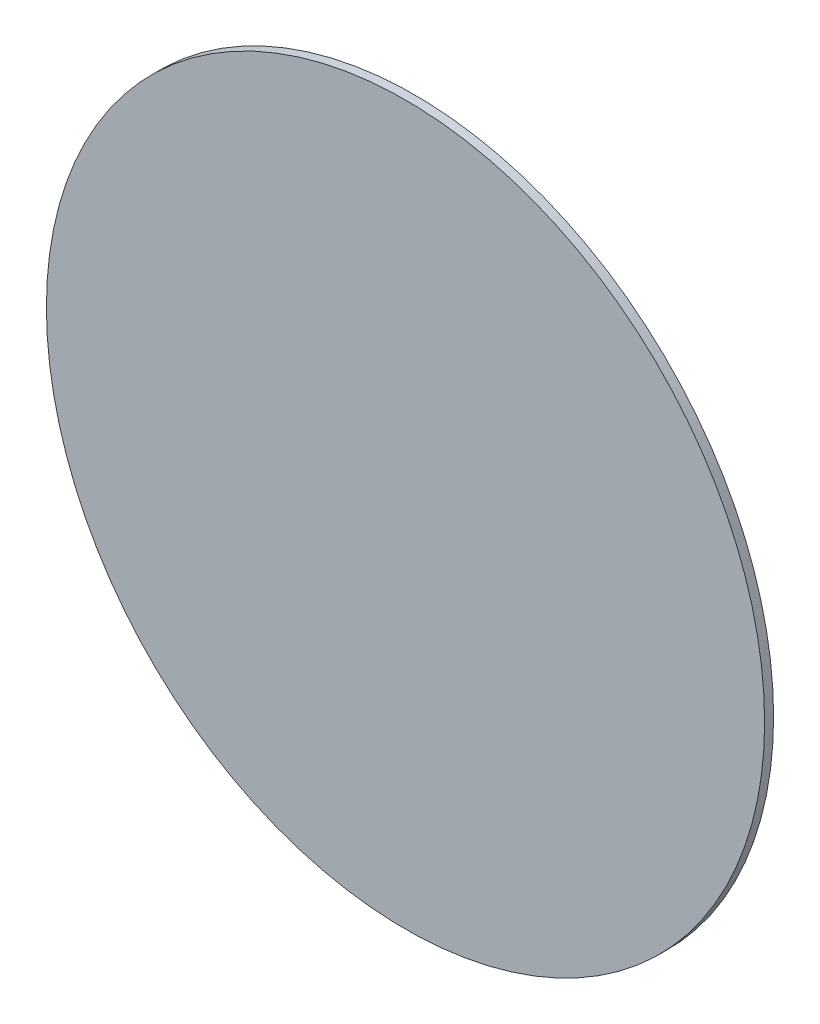
SolidWorks part; units mm, degrees
material "Silicon"
ref_plane "Front Plane" through (0, 0, 0) normal (0, 0, 1) x (1, 0, 0)
ref_plane "Top Plane" through (0, 0, 0) normal (0, 1, 0) x (1, 0, 0)
ref_plane "Right Plane" through (0, 0, 0) normal (1, 0, 0) x (0, 0, -1)
sketch "Sketch1" plane through (0, 0, 0) normal (0, 0, 1) x (1, 0, 0)
  circle A0 centre (0, 0) radius 4
  dimension "D1" = 8
extrude "Boss-Extrude1" add sketch "Sketch1" against normal blind 0.1
